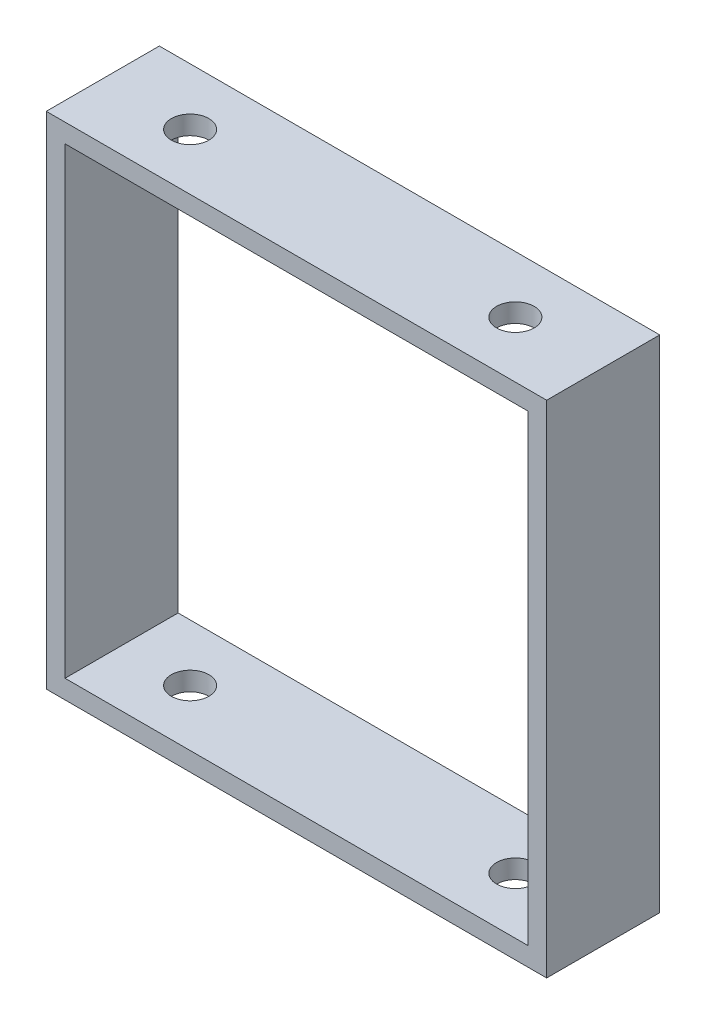
SolidWorks part; units mm, degrees
ref_plane "Front Plane" through (0, 0, 0) normal (0, 0, 1) x (1, 0, 0)
ref_plane "Top Plane" through (0, 0, 0) normal (0, 1, 0) x (1, 0, 0)
ref_plane "Right Plane" through (0, 0, 0) normal (1, 0, 0) x (0, 0, -1)
sketch "Sketch2" plane through (0, 0, 0) normal (0, 0, 1) x (1, 0, 0)
  line L1 (-63.5, 63.5) -> (63.5, 63.5)
  line L2 (-63.5, 63.5) -> (-63.5, -63.5)
  line L3 (-63.5, -63.5) -> (63.5, -63.5)
  line L4 (63.5, 63.5) -> (63.5, -63.5)
  line L5 (-63.5, 63.5) -> (63.5, -63.5) construction
  line L6 (-63.5, -63.5) -> (63.5, 63.5) construction
  point P0 (0, 0)
  dimension "D1" = 127
  dimension "D2" = 127
extrude "Boss-Extrude1" add sketch "Sketch2" along normal blind 28.702
sketch "Sketch3" plane through (0, 0, 28.702) normal (0, 0, 1) x (1, 0, 0)
  line L1 (-58.7375, 58.7375) -> (58.7375, 58.7375)
  line L2 (-58.7375, 58.7375) -> (-58.7375, -58.7375)
  line L3 (-58.7375, -58.7375) -> (58.7375, -58.7375)
  line L4 (58.7375, 58.7375) -> (58.7375, -58.7375)
  line L5 (-58.7375, 58.7375) -> (58.7375, -58.7375) construction
  line L6 (-58.7375, -58.7375) -> (58.7375, 58.7375) construction
  point P0 (0, 0)
  dimension "D1" = 117.475
  dimension "D2" = 117.475
extrude "Cut-Extrude1" cut sketch "Sketch3" against normal up to surface (28.702 mm away) up to face at (0, 0, 0)
sketch "Sketch4" plane through (0, 63.5, 0) normal (0, 1, 0) x (1, 0, 0)
  line L0 (63.5, -28.702) -> (63.5, 0) construction
  line L1 (63.5, -28.702) -> (-63.5, -28.702) construction
  line L2 (-63.5, -28.702) -> (-63.5, 0) construction
  circle A0 centre (41.275, -14.4145) radius 4.7625
  circle A1 centre (-41.275, -14.4145) radius 4.7625
  dimension "D2" = 14.2875
  dimension "D3" = 9.525
  dimension "D4" = 9.525
  dimension "D5" = 22.225
  dimension "D6" = 14.2875
  dimension "D1" = 22.225
extrude "Cut-Extrude2" cut sketch "Sketch4" against normal up to surface (127 mm away) up to face at (0, -63.5, 14.351)
